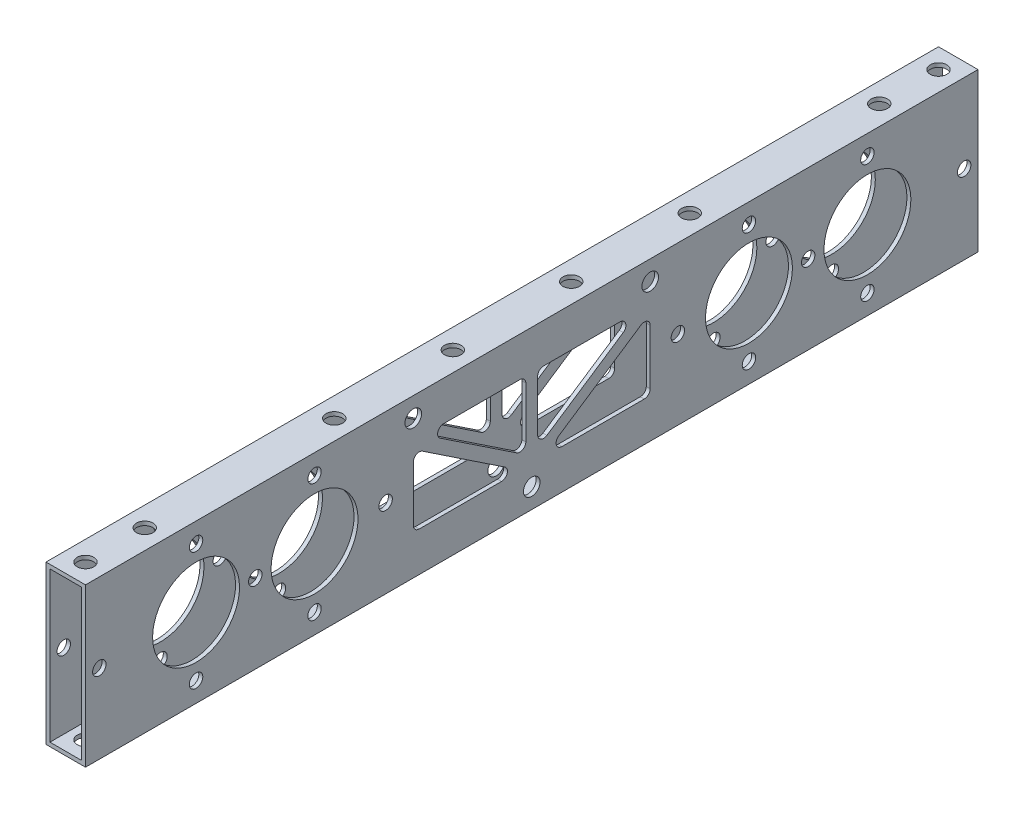
SolidWorks part; units mm, degrees
material "6061 合金"
ref_plane "前视基准面" through (0, 0, 0) normal (0, 0, 1) x (1, 0, 0)
ref_plane "上视基准面" through (0, 0, 0) normal (0, 1, 0) x (1, 0, 0)
ref_plane "右视基准面" through (0, 0, 0) normal (1, 0, 0) x (0, 0, -1)
sketch "草图1" plane through (0, 0, 0) normal (0, 0, 1) x (1, 0, 0)
  line L0 (-4, 19) -> (4, 19)
  line L1 (-5, 20) -> (5, 20)
  line L2 (-5, 20) -> (-5, -20)
  line L3 (-5, -20) -> (5, -20)
  line L4 (5, 20) -> (5, -20)
  line L5 (-5, 20) -> (5, -20) construction
  line L6 (-5, -20) -> (5, 20) construction
  line L7 (4, 19) -> (4, -19)
  line L8 (-4, -19) -> (4, -19)
  line L9 (-4, 19) -> (-4, -19)
  point P0 (0, 0)
  dimension "D1" = 10
  dimension "D2" = 40
  dimension "D3" = 1
extrude "凸台-拉伸1" add sketch "草图1" along normal mid plane 226
sketch "草图3" plane through (0, 0, 0) normal (1, 0, 0) x (0, 0, -1)
  line L0 (30, 15) -> (-30, 15) construction
  line L1 (-113, 20) -> (113, 20) construction
  line L2 (-113, -20) -> (113, -20) construction
  circle A0 centre (30, 15) radius 2.1
  circle A1 centre (-30, 15) radius 2.1
  circle A2 centre (0, -15) radius 2.1
  point P2 (0, 15)
  dimension "D3" = 4.2
  dimension "D1" = 60
  dimension "D2" = 5
  dimension "D4" = 5
extrude "切除-拉伸1" cut sketch "草图3" against normal mid plane 30
sketch "草图5" plane through (0, 0, 0) normal (0, 1, 0) x (1, 0, 0)
  line L0 (0, 30) -> (0, -30) construction
  line L1 (0, 45) -> (0, 15) construction
  line L2 (-5, -113) -> (-5, 113) construction
  line L3 (-5, 0) -> (5, 0) construction
  line L4 (5, -113) -> (5, 113) construction
  circle A0 centre (0, 15) radius 2.1
  circle A1 centre (0, 45) radius 2.1
  circle A2 centre (0, -45) radius 2.1
  circle A3 centre (0, -15) radius 2.1
  point P5 (0, 30)
  dimension "D3" = 4.2
  dimension "D1" = 60
  dimension "D2" = 30
extrude "切除-拉伸3" cut sketch "草图5" against normal mid plane 50
sketch "草图7" plane through (0, 0, 0) normal (1, 0, 0) x (0, 0, -1)
  line L0 (0, 10) -> (0, -10)
  line L1 (30, 10) -> (-30, 10)
  line L2 (30, 10) -> (30, -10)
  line L3 (30, -10) -> (-30, -10)
  line L4 (-30, 10) -> (-30, -10)
  line L5 (30, 10) -> (-30, -10) construction
  line L6 (30, -10) -> (-30, 10) construction
  line L7 (-30, 10) -> (0, -10)
  line L8 (30, 10) -> (0, -10)
  line L9 (-29.1679, 11.2481) -> (0.8321, -8.7519)
  line L10 (30.8321, 8.7519) -> (0.8321, -11.2481)
  line L11 (1.5, 10) -> (1.5, -10)
  line L12 (-30.8321, 8.7519) -> (-0.8321, -11.2481)
  line L13 (29.1679, 11.2481) -> (-0.8321, -8.7519)
  line L14 (-1.5, 10) -> (-1.5, -10)
  point P0 (0, 0)
  dimension "D1" = 60
  dimension "D2" = 20
  dimension "D3" = 1.5
  dimension "D4" = 1.5
extrude "切除-拉伸4" cut sketch "草图7" against normal mid plane 50 contours L14 L1 L9 | L13 L1 L11 | L2 L10 L3 | L12 L4 L3
fillet "圆角3" radius 1.5 12 edges at (4.5, 8.1972, 30) (4.5, -10, 2.7042) (4.5, 10, -1.5) (4.5, 10, -27.2958) (4.5, -7.1972, -1.5) (4.5, -10, -2.7042) (4.5, 8.1972, -30) (4.5, -10, -30) (4.5, 10, 27.2958) (4.5, 10, 1.5) (4.5, -7.1972, 1.5) (4.5, -10, 30)
fillet "圆角4" radius 1.5 12 edges at (-4.5, -10, 2.7042) (-4.5, -10, 30) (-4.5, 8.1972, 30) (-4.5, -10, -2.7042) (-4.5, 8.1972, -30) (-4.5, -7.1972, 1.5) (-4.5, 10, 27.2958) (-4.5, 10, 1.5) (-4.5, -7.1972, -1.5) (-4.5, 10, -1.5) (-4.5, 10, -27.2958) (-4.5, -10, -30)
sketch "草图10" plane through (0, 0, 0) normal (1, 0, 0) x (0, 0, -1)
  line L0 (-85, 0) -> (-55, 0) construction
  line L1 (55, 0) -> (85, 0) construction
  circle A0 centre (-85, 0) radius 11
  circle A1 centre (-55, 0) radius 11
  circle A2 centre (55, 0) radius 11
  circle A3 centre (85, 0) radius 11
  dimension "D5" = 22
  dimension "D1" = 30
  dimension "D2" = 30
  dimension "D3" = 55
  dimension "D4" = 55
extrude "切除-拉伸6" cut sketch "草图10" against normal mid plane 50
sketch "草图11" plane through (0, -20, 0) normal (0, -1, 0) x (1, 0, 0)
  circle A0 centre (0, 0) radius 2.05
  dimension "D1" = 4.1
extrude "切除-拉伸7" cut sketch "草图11" against normal up to next
sketch "草图12" plane through (0, 20, 0) normal (0, 1, 0) x (1, 0, 0)
  line L0 (0, 108) -> (0, -108) construction
  line L1 (5, 113) -> (-5, 113) construction
  circle A0 centre (0, 108) radius 2.1
  circle A1 centre (0, 93) radius 2.1
  circle A2 centre (0, -108) radius 2.1
  circle A3 centre (0, -93) radius 2.1
  dimension "D4" = 4.2
  dimension "D1" = 5
  dimension "D2" = 15
  dimension "D3" = 15
extrude "切除-拉伸8" cut sketch "草图12" against normal through all
sketch "草图14" plane through (5, 0, 0) normal (1, 0, 0) x (0, 0, -1)
  line L1 (110.2889, 15.9865) -> (-109.7111, 15.9865)
  line L2 (110.2889, 15.9865) -> (110.2889, -16.0707)
  line L3 (110.2889, -16.0707) -> (-109.7111, -16.0707)
  line L4 (-109.7111, 15.9865) -> (-109.7111, -16.0707)
  line L5 (110.2889, 15.9865) -> (-109.7111, -16.0707) construction
  line L6 (110.2889, -16.0707) -> (-109.7111, 15.9865) construction
  point P0 (0.2889, -0.0421)
  dimension "D1" = 110
sketch "草图15" plane through (6.5, 0, 0) normal (1, 0, 0) x (0, 0, -1)
  line L22 (201.5, -4.3944) -> (201.5, 8.5) construction
  circle A9 centre (0, -15) radius 2.1
  circle A19 centre (30, 15) radius 2.1
  circle A33 centre (-30, 15) radius 2.1
  circle A40 centre (-37, 0) radius 1.7
  circle A42 centre (37, 0) radius 1.7
  circle A44 centre (70, 0) radius 1.7
  circle A46 centre (-109.5, 0) radius 1.7
  circle A48 centre (-85, -15) radius 1.7
  circle A50 centre (109.5, 0) radius 1.7
  circle A52 centre (-55, 15) radius 1.7
  circle A54 centre (-70, 0) radius 1.7
  circle A72 centre (55, 15) radius 1.7
  circle A74 centre (-55, -15) radius 1.7
  circle A76 centre (85, 15) radius 1.7
  circle A78 centre (-85, 15) radius 1.7
  circle A80 centre (55, -15) radius 1.7
  circle A82 centre (85, -15) radius 1.7
  point P0 (0, 0)
  dimension "D1" = 4.2
  dimension "D2" = 3.4
  dimension "D3" = 92
  dimension "D4" = 116.5
  dimension "D5" = 131.5
  dimension "D6" = 146.5
  dimension "D7" = 164.5
  dimension "D8" = 171.5
  dimension "D9" = 201.5
  dimension "D10" = 231.5
  dimension "D11" = 238.5
  dimension "D12" = 256.5
  dimension "D13" = 271.5
  dimension "D14" = 286.5
  dimension "D15" = 311
  dimension "D16" = 5
  dimension "D17" = 10
  dimension "D18" = 25
extrude "切除-拉伸9" cut sketch "草图15" against normal through all
